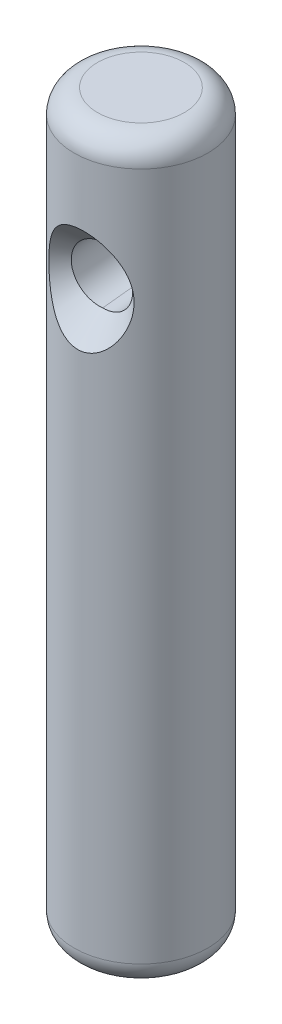
SolidWorks part; units mm, degrees
ref_plane "Front Plane" through (0, 0, 0) normal (0, 0, 1) x (1, 0, 0)
ref_plane "Top Plane" through (0, 0, 0) normal (0, 1, 0) x (1, 0, 0)
ref_plane "Right Plane" through (0, 0, 0) normal (1, 0, 0) x (0, 0, -1)
sketch "Sketch1" plane through (0, 0, 0) normal (0, 1, 0) x (1, 0, 0)
  circle A0 centre (0, 0) radius 4
  dimension "D1" = 8
extrude "Boss-Extrude1" add sketch "Sketch1" along normal blind 44
fillet "Fillet3" radius 1.4 2 edges at (0, 44, 4) (0, 0, 4)
hole_wizard "CSK for M3 Oval Head Machine Screw1" positions "3DSketch2" profile "Sketch6" countersink size "M3" standard "ANSI Metric" end condition through all
sketch3d "3DSketch2"
  circle A0 centre (0, 42.6, 0) radius 4 construction
  point P0 (0.3117, 35.6718, 3.9878)
  point P3 (0.3117, 35.6718, 3.9878)
  point P5 (-0.4772, 35.6718, -3.9714)
  point P10 (0, 38.6, 0)
  dimension "D1" = 8
  dimension "D2" = 8
sketch "Sketch6" plane through (0.3117, 35.6718, 3.9878) normal (0, 1, 0) x (0.997, 0, -0.0779)
  line L0 (0, 0) -> (0, 8)
  line L1 (0, 8) -> (1.725, 8)
  line L2 (1.7, 7.975) -> (1.7, 1.45)
  line L3 (1.7, 1.45) -> (3.15, 0)
  line L5 (3.15, 0) -> (0, 0)
  line L6 (-1.7, 1.45) -> (-3.15, 0) construction
  line L7 (1.725, 8) -> (1.7, 7.975)
  line L8 (-1.725, 8) -> (-1.7, 7.975) construction
  line L11 (0, -6.35) -> (0, 107.95) construction
  dimension "Thru Hole Dia." = 3.4
  dimension "Thru Hole Depth" = 8
  dimension "Near C'Sink Dia." = 6.3
  dimension "Near C'Sink Angle" = 90
  dimension "Far C'Sink Dia." = 3.45
  dimension "Far C'Sink Angle" = 90
